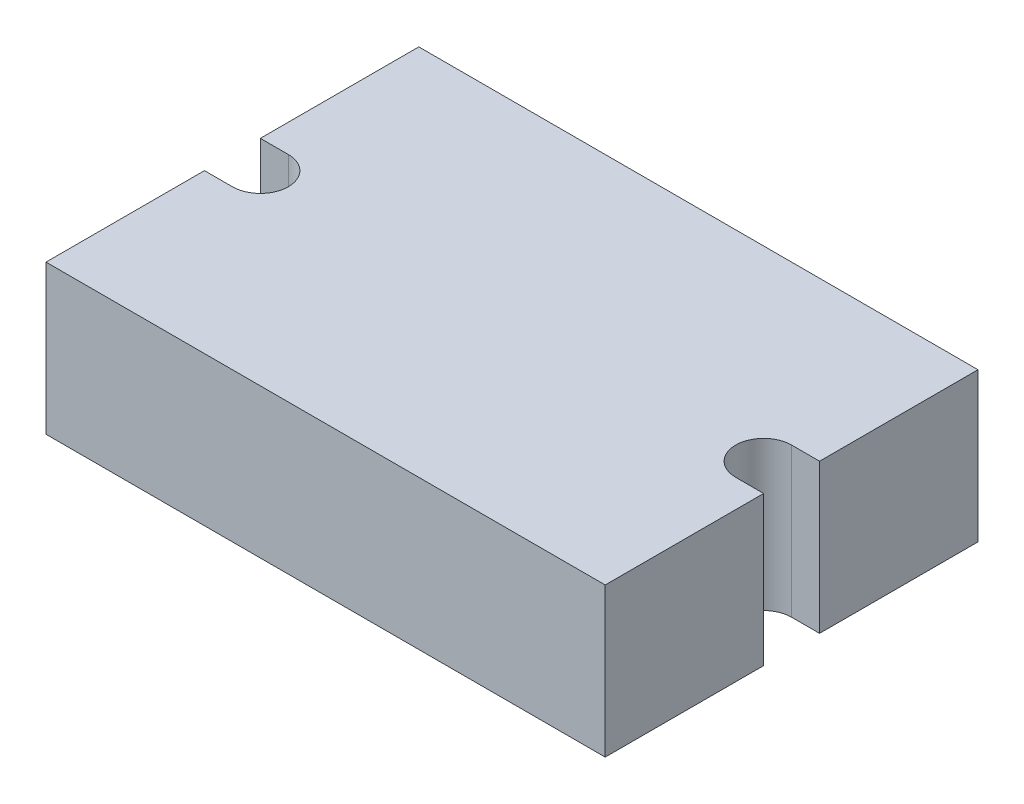
SolidWorks part; units mm, degrees
ref_plane "Płaszczyzna przednia" through (0, 0, 0) normal (0, 0, 1) x (1, 0, 0)
ref_plane "Płaszczyzna górna" through (0, 0, 0) normal (0, 1, 0) x (1, 0, 0)
ref_plane "Płaszczyzna prawa" through (0, 0, 0) normal (1, 0, 0) x (0, 0, -1)
sketch "Szkic1" plane through (0, 0, 0) normal (0, 1, 0) x (1, 0, 0)
  line L1 (0, 0) -> (30, 0)
  line L3 (0, 20) -> (30, 20)
  line L11 (28.5, 8.5) -> (30, 8.5)
  line L12 (28.5, 11.5) -> (30, 11.5)
  line L13 (30, 11.5) -> (30, 20)
  line L14 (30, 8.5) -> (30, 0)
  line L16 (0, 11.5) -> (0, 20)
  line L18 (0, 8.5) -> (0, 0)
  line L19 (1.5, 8.5) -> (0, 8.5)
  line L20 (1.5, 11.5) -> (0, 11.5)
  arc A0 (28.5, 8.5) -> (28.5, 11.5) centre (28.5, 10) cw
  arc A1 (1.5, 8.5) -> (1.5, 11.5) centre (1.5, 10) ccw
extrude "Dodanie-wyciągnięcie1" add sketch "Szkic1" along normal blind 8
